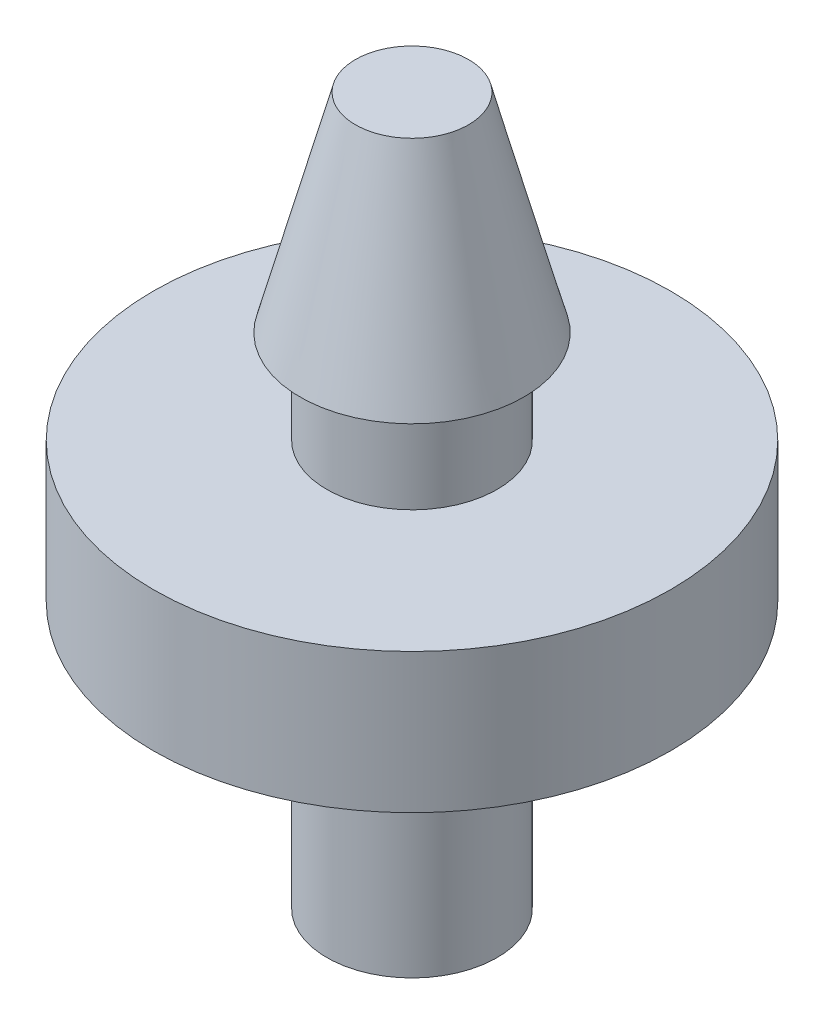
SolidWorks part; units mm, degrees
ref_plane "Front Plane" through (0, 0, 0) normal (0, 0, 1) x (1, 0, 0)
ref_plane "Top Plane" through (0, 0, 0) normal (0, 1, 0) x (1, 0, 0)
ref_plane "Right Plane" through (0, 0, 0) normal (1, 0, 0) x (0, 0, -1)
sketch "Sketch1" plane through (0, 0, 0) normal (0, 0, 1) x (1, 0, 0)
  line L0 (0, -0.0959) -> (0, 3.2077) construction
  line L1 (0, 0) -> (-2.025, 0)
  line L2 (-2.025, 0) -> (-2.025, 6.32)
  line L3 (-2.025, 6.32) -> (-6.15, 6.32)
  line L4 (-6.15, 6.32) -> (-6.15, 9.64)
  line L5 (-6.15, 9.64) -> (-2.025, 9.64)
  line L6 (-2.025, 9.64) -> (-2.025, 11.86)
  line L7 (-2.025, 11.86) -> (-2.66, 11.86)
  line L8 (-2.66, 11.86) -> (-1.345, 16.81)
  line L9 (-1.345, 16.81) -> (0, 16.81)
  line L10 (0, 16.81) -> (0, 0)
  line L11 (-0.94, 16.81) -> (-0.94, 0)
  dimension "D1" = 6.15
  dimension "D2" = 2.025
  dimension "D3" = 2.66
  dimension "D4" = 1.345
  dimension "D5" = 6.32
  dimension "D6" = 3.32
  dimension "D7" = 2.22
  dimension "D8" = 4.95
  dimension "D9" = 0.94
revolve "Revolve1" add sketch "Sketch1" angle 360 about L0
